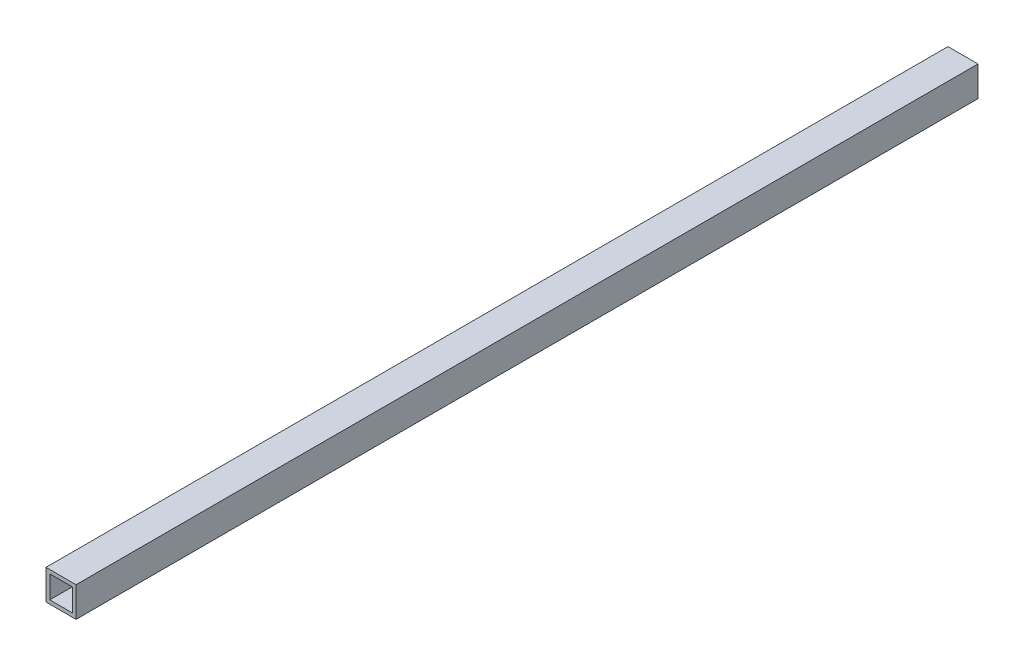
SolidWorks part; units mm, degrees
material "1060 Alloy"
ref_plane "Front Plane" through (0, 0, 0) normal (0, 0, 1) x (1, 0, 0)
ref_plane "Top Plane" through (0, 0, 0) normal (0, 1, 0) x (1, 0, 0)
ref_plane "Right Plane" through (0, 0, 0) normal (1, 0, 0) x (0, 0, -1)
sketch "Sketch1" plane through (0, 0, 0) normal (0, 0, 1) x (1, 0, 0)
  line L1 (0, 0) -> (25.4, 0)
  line L2 (0, 0) -> (0, 25.4)
  line L3 (0, 25.4) -> (25.4, 25.4)
  line L4 (25.4, 0) -> (25.4, 25.4)
  line L5 (3.175, 3.175) -> (22.225, 3.175)
  line L6 (3.175, 3.175) -> (3.175, 22.225)
  line L7 (3.175, 22.225) -> (22.225, 22.225)
  line L8 (22.225, 3.175) -> (22.225, 22.225)
  dimension "D1" = 25.4
  dimension "D2" = 25.4
  dimension "D3" = 3.175
  dimension "D4" = 3.175
  dimension "D5" = 3.175
  dimension "D6" = 3.175
extrude "Boss-Extrude1" add sketch "Sketch1" along normal blind 762
